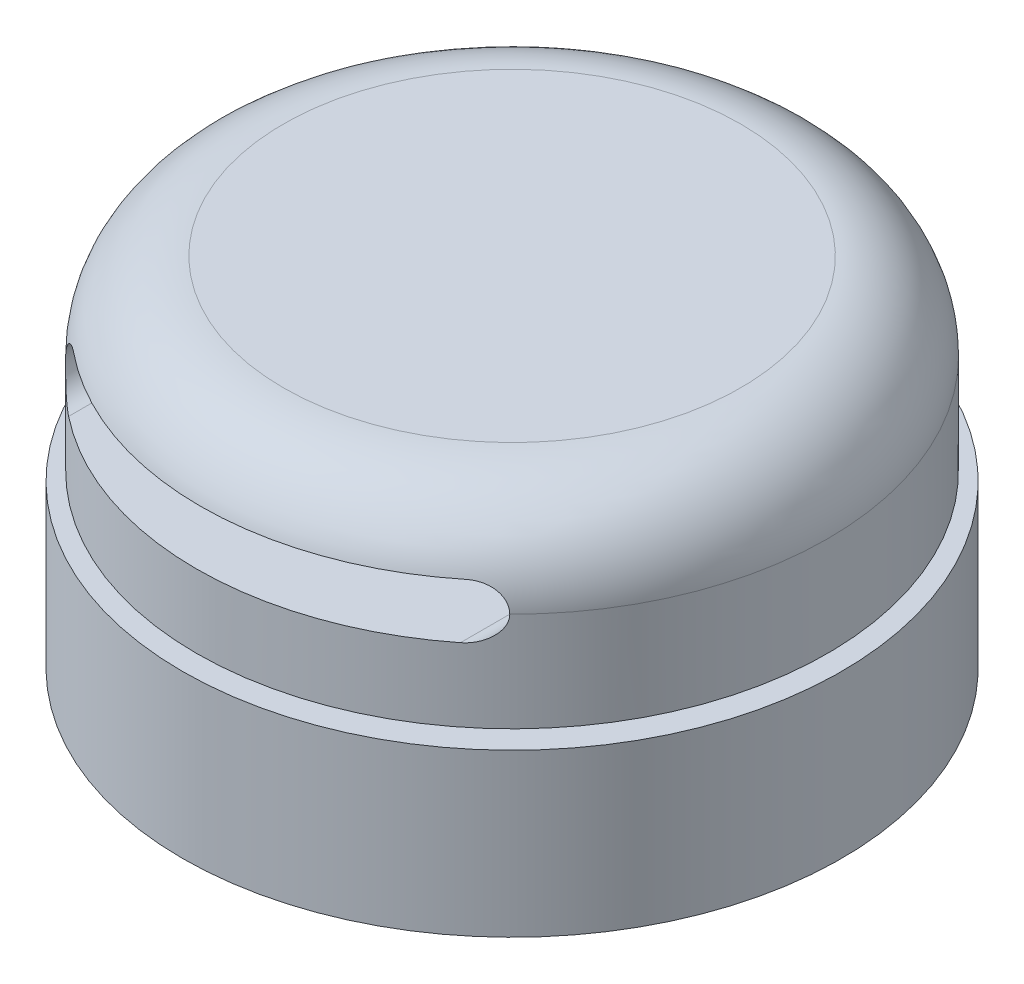
SolidWorks part; units mm, degrees
ref_plane "前视基准面" through (0, 0, 0) normal (0, 0, 1) x (1, 0, 0)
ref_plane "上视基准面" through (0, 0, 0) normal (0, 1, 0) x (1, 0, 0)
ref_plane "右视基准面" through (0, 0, 0) normal (1, 0, 0) x (0, 0, -1)
sketch "草图1" plane through (0, 0, 0) normal (0, 0, 1) x (1, 0, 0)
  line L0 (0, 49.4448) -> (0, -31.1725) construction
  line L1 (0, 0) -> (-37.845, 0)
  line L2 (-37.845, 0) -> (-37.845, 18.6)
  line L3 (-37.845, 18.6) -> (-34, 18.6)
  line L4 (-34, 18.6) -> (-34, 19.6)
  line L5 (-34, 19.6) -> (-36.25, 19.6)
  line L6 (-36.25, 19.6) -> (-36.25, 41)
  line L7 (-36.25, 41) -> (0, 41)
  line L8 (0, 0) -> (0, 41)
  dimension "D1" = 72.5
  dimension "D2" = 41
  dimension "D3" = 18.6
  dimension "D4" = 19.6
  dimension "D5" = 75.69
  dimension "D6" = 68
revolve "旋转1" add sketch "草图1" angle 360 about L0
sketch "草图2" plane through (0, 0, 0) normal (0, -1, 0) x (1, 0, 0)
  circle A0 centre (0, 0) radius 29.5 construction
  circle A1 centre (0, 29.5) radius 1.5
  dimension "D1" = 59
  dimension "D2" = 3
extrude "切除-拉伸1" cut sketch "草图2" against normal blind 1
sketch "草图3" plane through (0, 0, 0) normal (0, -1, 0) x (1, 0, 0)
  line L0 (-20.8597, 20.8597) -> (0, 0) construction
  line L1 (0, 0) -> (-22.4528, 0) construction
  circle A0 centre (0, 0) radius 29.5 construction
  dimension "D1" = 59
  dimension "D2" = 45
hole_wizard "g" positions "3D草图1" profile "草图4" tap size "M3" standard "GB"
sketch3d "3D草图1"
  point P0 (-20.8597, 0, 20.8597)
sketch "草图4" plane through (-20.8597, 0, 20.8597) normal (1, 0, 0) x (0, 0, -1)
  line L0 (0, 0) -> (0, 8.2511)
  line L1 (0, 8.2511) -> (1.25, 7.5)
  line L2 (1.25, 7.5) -> (1.25, 0)
  line L5 (1.25, 0) -> (0, 0)
  line L10 (0, 8.2511) -> (-1.25, 7.5) construction
  line L11 (0, -6.35) -> (0, 107.95) construction
  dimension "螺纹孔钻头直径" = 2.5
  dimension "螺纹孔钻头深度" = 7.5
  dimension "导头角度" = 118
cosmetic thread "孔螺蚊线1" parameters "D1"=6, "D2"=3
pattern_circular "阵列(圆周)1" count 4 over 360 about axis through (0, 0, 0) along (0, 1, 0) of "g"
fillet "圆角1" radius 10 1 edges at (0, 41, 36.25)
sketch "草图5" plane through (0, 0, 0) normal (0, 0, 1) x (1, 0, 0)
  line L0 (-22.5, 31) -> (22.5, 31) construction
  line L1 (-22.5, 34) -> (22.5, 34)
  line L2 (-22.5, 28) -> (22.5, 28)
  line L3 (-37.845, 0) -> (37.845, 0) construction
  line L4 (0, 31) -> (0, 0) construction
  arc A0 (-22.5, 34) -> (-22.5, 28) centre (-22.5, 31) ccw
  arc A1 (22.5, 28) -> (22.5, 34) centre (22.5, 31) ccw
  point P2 (0, 31)
  dimension "D1" = 6
  dimension "D2" = 31
  dimension "D3" = 45
extrude "切除-拉伸2" cut sketch "草图5" along normal through all
